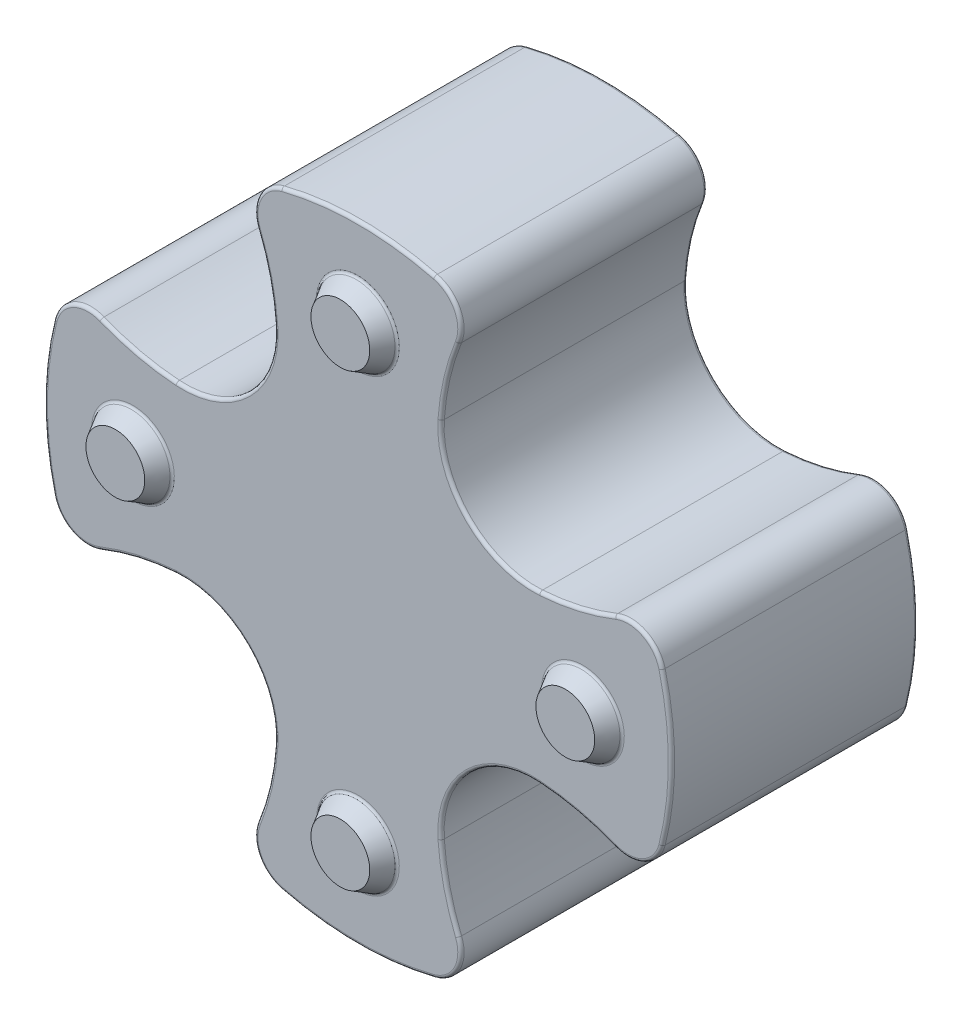
SolidWorks part; units mm, degrees
ref_plane "Front Plane" through (0, 0, 0) normal (0, 0, 1) x (1, 0, 0)
ref_plane "Top Plane" through (0, 0, 0) normal (0, 1, 0) x (1, 0, 0)
ref_plane "Right Plane" through (0, 0, 0) normal (1, 0, 0) x (0, 0, -1)
sketch "Sketch1" plane through (0, 0, 0) normal (0, 0, 1) x (1, 0, 0)
  line L0 (0, 13.1493) -> (0, 6.35) construction
  line L2 (0, 6.35) -> (0, 0) construction
  line L3 (-3.429, 13.1493) -> (3.429, 13.1493) construction
  line L7 (0, -13.589) -> (0, 0)
  line L9 (-3.429, 13.1493) -> (-3.429, 5.3446) construction
  line L10 (3.429, 13.1493) -> (3.429, 5.3446) construction
  circle A0 centre (0, 0) radius 13.589 construction
  circle A1 centre (0, 0) radius 6.35 construction
  circle A4 centre (0, 9.7496) radius 1.7145 construction
  circle A6 centre (0, 0) radius 9.7496 construction
  dimension "OD A" = 27.178
  dimension "D3" = 3.429
  dimension "ID H" = 12.7
  dimension "Arm Width B" = 6.858
sketch "Sketch2" plane through (0, 0, 0) normal (1, 0, 0) x (0, 0, -1)
  line L1 (-5.334, -13.589) -> (5.334, -13.589) construction
  line L2 (-5.334, -13.589) -> (-5.334, 13.589) construction
  line L3 (-5.334, 13.589) -> (5.334, 13.589) construction
  line L4 (5.334, -13.589) -> (5.334, 13.589) construction
  line L5 (0, 13.589) -> (0, -13.589) construction
  line L6 (-5.334, 0) -> (5.334, 0) construction
  point P0 (4.318, 0)
  dimension "Width W" = 10.668
  dimension "Center Offset DD" = 9.652
sketch "Sketch3" plane through (0, 0, 0) normal (0, 0, 1) x (1, 0, 0)
  line L1 (-4.7685, 4.7685) -> (-7.5964, 7.5964) construction
  line L3 (0, 0) -> (-4.7685, 4.7685)
  line L4 (4.7685, 4.7685) -> (0, 0)
  line L5 (4.7685, 4.7685) -> (7.5964, 7.5964) construction
  line L6 (-4.7685, 4.7685) -> (4.7685, 4.7685) construction
  line L8 (0, 13.589) -> (0, 0) construction
  circle A0 centre (0, 0) radius 13.589 construction
  circle A65 centre (0, 0) radius 9.7496 construction
  arc A98 (3.6066, 7.8707) -> (4.7685, 4.7685) centre (7.5964, 7.5964) ccw
  arc A99 (4.3554, 11.1316) -> (3.6066, 7.8707) centre (14.2748, 7.1374) ccw
  arc A100 (4.3554, 11.1316) -> (3.3133, 13.1789) centre (2.9417, 11.7009) ccw
  arc A101 (3.3133, 13.1789) -> (-3.3133, 13.1789) centre (0, 0) ccw
  arc A102 (-3.3133, 13.1789) -> (-4.3554, 11.1316) centre (-2.9417, 11.7009) ccw
  arc A103 (-3.6066, 7.8707) -> (-4.3554, 11.1316) centre (-14.2748, 7.1374) ccw
  arc A104 (-4.7685, 4.7685) -> (-3.6066, 7.8707) centre (-7.5964, 7.5964) ccw
  circle A127 centre (0, 0) radius 9.7496 construction
  point P0 (-9.6089, 9.6089)
  point P6 (9.6089, 9.6089)
  dimension "D2" = 6.8453
  dimension "D3" = 9.5831
  dimension "D4" = 1.524
  dimension "D5" = 10.6934
  dimension "D6" = 3.9993
  dimension "D1" = 90
  dimension "D7" = 9.5831
extrude "Boss-Extrude1" add sketch "Sketch3" along normal up to vertex (5.334 mm away) up to point (0, 0, 5.334)
sketch "Sketch5" plane through (0, 0, 5.334) normal (0, 0, 1) x (1, 0, 0)
  circle A3 centre (0, 9.7496) radius 1.7145
  circle A4 centre (0, 9.7496) radius 1.7145 construction
extrude "Boss-Extrude3" add sketch "Sketch5" along normal blind 0.762 draft 30
pattern_circular "CirPattern1" count 4 over 360 about axis through (0, 0, 0) along (0, 0, 1) of bodies 116 104
combine bodies "Combine1" bodies to combine 105 116 107 106
fillet "Fillet3" radius 0.1372 28 edges at (-12.3922, 4.2999, 5.334) (-13.589, 0, 5.334) (-12.3922, -4.2999, 5.334) (-9.5306, -3.8526, 5.334) (-4.7685, -4.7685, 5.334) (-9.7496, 1.7145, 5.334) (-4.7685, 4.7685, 5.334) (4.7685, 4.7685, 5.334) (3.8526, 9.5306, 5.334) (4.2999, 12.3922, 5.334) (0, 13.589, 5.334) (-4.2999, 12.3922, 5.334) (-3.8526, 9.5306, 5.334) (-3.8526, -9.5306, 5.334) (-4.2999, -12.3922, 5.334) (0, -13.589, 5.334) (4.2999, -12.3922, 5.334) (3.8526, -9.5306, 5.334) (4.7685, -4.7685, 5.334) (9.5306, -3.8526, 5.334) (12.3922, -4.2999, 5.334) (13.589, 0, 5.334) (12.3922, 4.2999, 5.334) (9.5306, 3.8526, 5.334) (1.7145, 9.7496, 5.334) (9.7496, -1.7145, 5.334) (-1.7145, -9.7496, 5.334) (-9.5306, 3.8526, 5.334)
mirror "Mirror1" about plane through (-7.5964, 7.5964, 0) normal (0, 0, 1) of bodies 110 111
equation "\"D3@Sketch1\"=\"Arm Width B@Sketch1\"*.5"
equation "\"D1@Fillet3\"=\"Arm Width B@Sketch1\"*.02"
